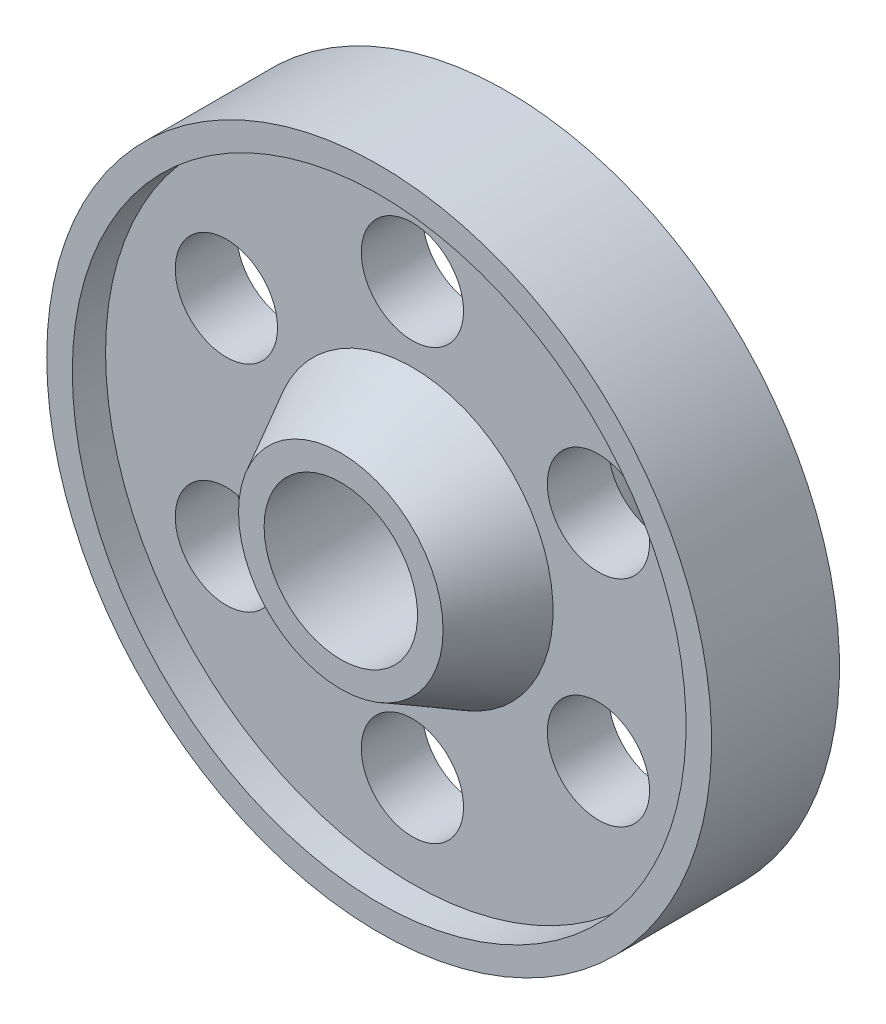
SolidWorks part; units mm, degrees
material "Gray Cast Iron (SN)"
ref_plane "Front Plane" through (0, 0, 0) normal (0, 0, 1) x (1, 0, 0)
ref_plane "Top Plane" through (0, 0, 0) normal (0, 1, 0) x (1, 0, 0)
ref_plane "Right Plane" through (0, 0, 0) normal (1, 0, 0) x (0, 0, -1)
sketch "Sketch1" plane through (0, 0, 0) normal (1, 0, 0) x (0, 0, -1)
  line L0 (0, 0) -> (0, 65) construction
  line L1 (12.5, 65) -> (-12.5, 65)
  line L2 (-12.5, 65) -> (-12.5, 60)
  line L3 (12.5, 65) -> (12.5, 60)
  line L4 (-12.5, 60) -> (-6, 60)
  line L5 (12.5, 60) -> (6, 60)
  line L6 (-6, 60) -> (-6, 41.9643)
  line L7 (6, 60) -> (6, 41.9643)
  line L9 (20, 15) -> (-20, 15)
  line L10 (-20, 15) -> (-20, 20)
  line L11 (20, 15) -> (20, 20)
  line L12 (-20, 20) -> (-6, 27.5)
  line L13 (20, 20) -> (6, 27.5)
  line L14 (-6, 27.5) -> (-6, 41.9643)
  line L15 (6, 27.5) -> (6, 41.9643)
  line L17 (27.7058, 0) -> (-53.8531, 0) construction
  line L18 (-27.7058, 0) -> (53.8531, 0) construction
  point P3 (0, 15)
  point P12 (0, 41.9643)
  point P16 (0, 15)
  point P23 (0, 41.9643)
  dimension "D1" = 65
  dimension "D2" = 15
  dimension "D3" = 25
  dimension "D4" = 12
  dimension "D5" = 60
  dimension "D6" = 27.5
  dimension "D7" = 20
  dimension "D8" = 40
revolve "Revolve1" add sketch "Sketch1" angle 360 about L17
sketch "Sketch2" plane through (0, 0, 6) normal (0, 0, 1) x (1, 0, 0)
  circle A0 centre (0, 0) radius 42 construction
  circle A1 centre (0, 42) radius 10
  circle A2 centre (0, 0) radius 42 construction
  circle A3 centre (36.3731, 21) radius 10
  circle A4 centre (0, 0) radius 42 construction
  circle A5 centre (36.3731, -21) radius 10
  circle A6 centre (0, 0) radius 42 construction
  circle A7 centre (0, -42) radius 10
  circle A8 centre (0, 0) radius 42 construction
  circle A9 centre (-36.3731, -21) radius 10
  circle A10 centre (0, 0) radius 42 construction
  circle A11 centre (-36.3731, 21) radius 10
  point P23 (0, 0)
  dimension "D1" = 84
  dimension "D2" = 20
  dimension "D3" = 6
extrude "Cut-Extrude1" cut sketch "Sketch2" against normal through all both and the other way through all
